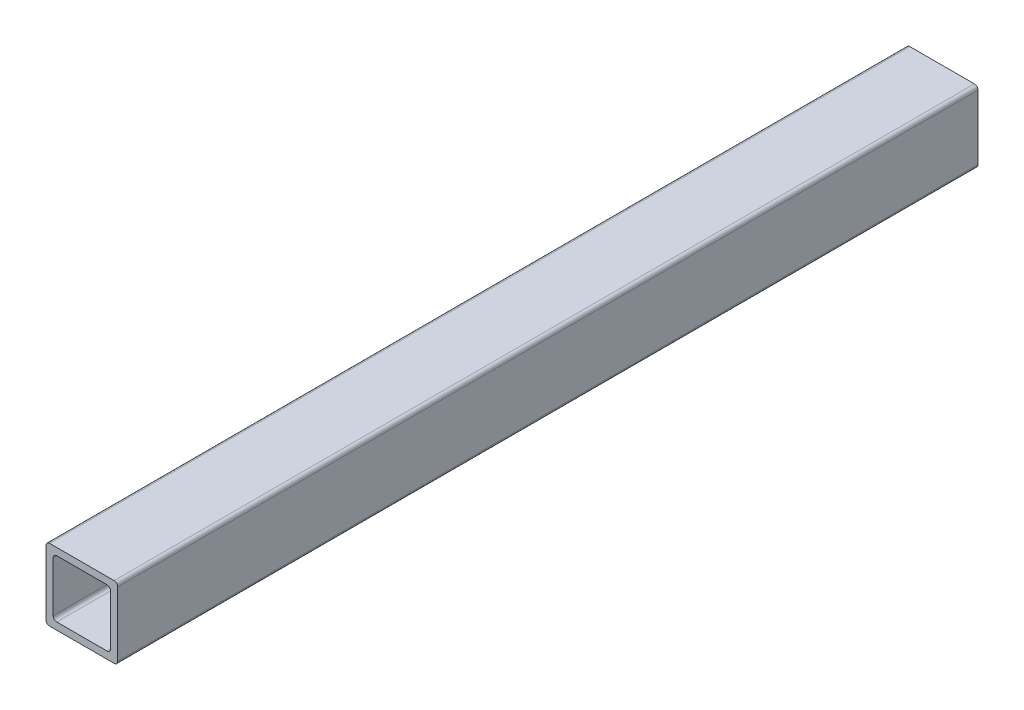
SolidWorks part; units mm, degrees
ref_plane "Plan de face" through (0, 0, 0) normal (0, 0, 1) x (1, 0, 0)
ref_plane "Plan de dessus" through (0, 0, 0) normal (0, 1, 0) x (1, 0, 0)
ref_plane "Plan de droite" through (0, 0, 0) normal (1, 0, 0) x (0, 0, -1)
sketch "Esquisse2" plane through (0, 0, 0) normal (0, 0, 1) x (1, 0, 0)
  line L0 (6, 4) -> (34, 4)
  line L1 (2, 0) -> (38, 0)
  line L2 (0, 2) -> (0, 38)
  line L3 (2, 40) -> (38, 40)
  line L4 (40, 2) -> (40, 38)
  line L5 (36, 6) -> (36, 34)
  line L6 (6, 36) -> (34, 36)
  line L7 (4, 6) -> (4, 34)
  line L8 (4, 4) -> (36, 4) construction
  line L9 (36, 4) -> (36, 36) construction
  line L10 (4, 36) -> (36, 36) construction
  line L11 (4, 4) -> (4, 36) construction
  line L12 (0, 0) -> (40, 0) construction
  line L13 (0, 0) -> (0, 40) construction
  line L14 (0, 40) -> (40, 40) construction
  line L15 (40, 0) -> (40, 40) construction
  arc A0 (34, 4) -> (36, 6) centre (34, 6) ccw
  arc A1 (36, 34) -> (34, 36) centre (34, 34) ccw
  arc A2 (6, 36) -> (4, 34) centre (6, 34) ccw
  arc A3 (4, 6) -> (6, 4) centre (6, 6) ccw
  arc A4 (2, 0) -> (0, 2) centre (2, 2) cw
  arc A5 (0, 38) -> (2, 40) centre (2, 38) cw
  arc A6 (38, 40) -> (40, 38) centre (38, 38) cw
  arc A7 (40, 2) -> (38, 0) centre (38, 2) cw
  point P24 (0, 0)
  dimension "D4" = 2
  dimension "D1" = 40
  dimension "D2" = 40
  dimension "D3" = 4
extrude "Boss.-Extru.1" add sketch "Esquisse2" along normal blind 480
